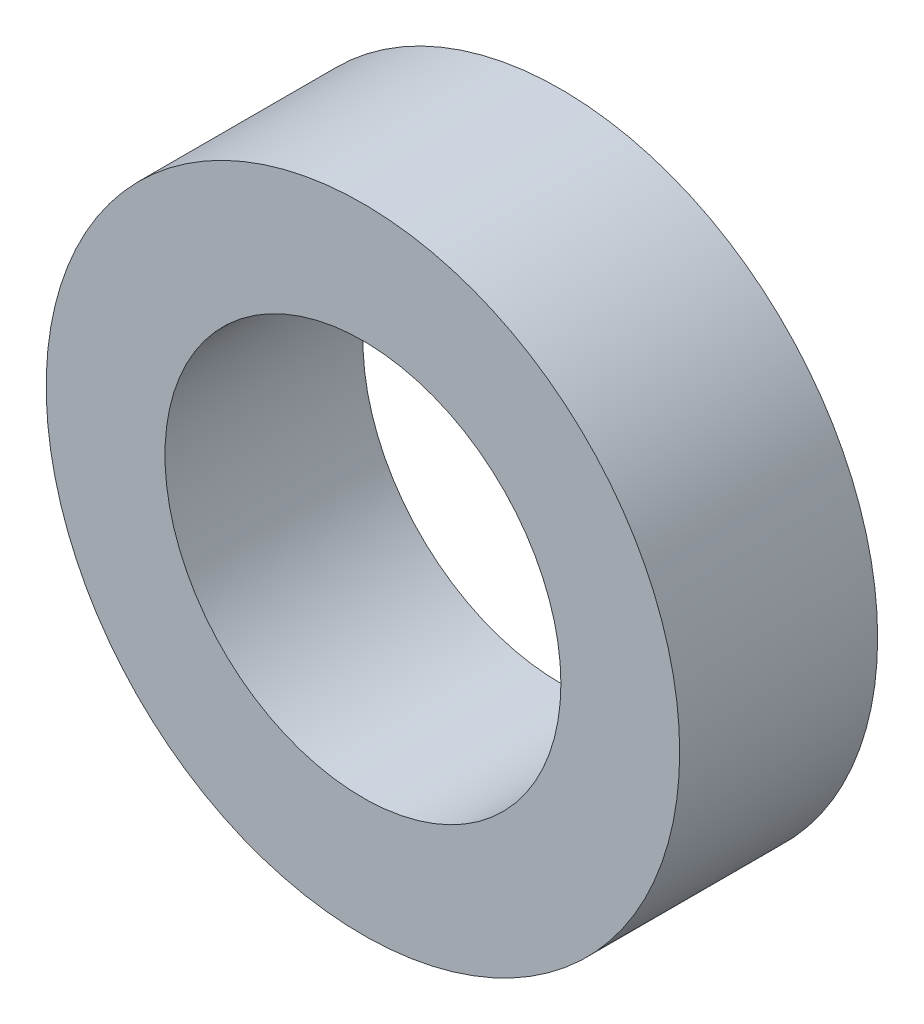
SolidWorks part; units mm, degrees
ref_plane "Front Plane" through (0, 0, 0) normal (0, 0, 1) x (1, 0, 0)
ref_plane "Top Plane" through (0, 0, 0) normal (0, 1, 0) x (1, 0, 0)
ref_plane "Right Plane" through (0, 0, 0) normal (1, 0, 0) x (0, 0, -1)
sketch "Sketch1" plane through (0, 0, 0) normal (0, 0, 1) x (1, 0, 0)
  circle A0 centre (0, 0) radius 4
  circle A1 centre (0, 0) radius 2.5
  dimension "D1" = 5
  dimension "D2" = 8
extrude "Boss-Extrude1" add sketch "Sketch1" along normal blind 2.5
equation "\"Ns\"= 24"
equation "\"Nr\"= 78"
equation "\"num_planet\"= 3"
equation "\"module\"= 0.6"
equation "\"pressure angle\"= 20.0"
equation "\"h_a\"= 0.6"
equation "\"h_b\"= 0.75"
equation "\"clr_tip_root\"= 0.15000000000000002"
equation "\"dp_s\"= 14.399999999999999"
equation "\"db_s\"= 13.53157373931708"
equation "\"fw_s_calc\"= 16.210783717444997"
equation "\"alpha_s\"= 0.8539582918412343"
equation "\"beta_s\"= 5.792083416317531"
equation "\"pressure_angle\"= 20.0"
equation "\"h_f\"= 0.75"
equation "\"dp_r\"= 46.8"
equation "\"db_r\"= 43.97761465278051"
equation "\"fw_r\"= 22.845791438896047"
equation "\"alpha_r\"= 0.8539582918412556"
equation "\"beta_r\"= 4.015608891374819"
equation "\"bearing_ID\"= 45"
equation "\"bearing_OD\"= 58"
equation "\"bearing_height\"= 7"
equation "\"clearance_planet\"= 1.5"
equation "\"case_dist\"= 24.210783717444997"
equation "\"Motor_case_OD_max\"= 88.5"
equation "\"case_mounting_PCD\"= 81.0"
equation "\"bearing mount thickness\"= IIF((\"bearing_OD\" + \"output_mounting_hole_dia\" * 4) > (\"Nr\" * \"module\" + 2 * \"h_b\"), \"output_mounting_hole_dia\" * 2, ((\"Nr\" * \"module\" + 2 * \"h_b\" - (\"bearing_OD\" + \"output_mounting_hole_dia\" * 4)) / 2) + \"output_mounting_hole_dia\" * 2 + \"standard_clearance_1_5mm\")"
equation "\"case_mounting_hole_dia\"= 3"
equation "\"output_mounting_PCD\"= 66"
equation "\"output_mounting_hole_dia\"= 4"
equation "\"clearance_case_mount_holes_shell_thickness\"= 1"
equation "\"motor_case_OD_base\"= 79.0"
equation "\"sec_carrier_thickness\"= 5"
equation "\"sun_coupler_hub_thickness\"= 4"
equation "\"clearance_sun_coupler_sec_carrier\"= 1.5"
equation "\"clearance_motor_and_case\"= 5"
equation "\"motor_OD\"= 64"
equation "\"Motor_case_thickness\"= 2.5"
equation "\"Motor_case_ID\"= 74"
equation "\"case_mounting_hole_shift\"= 1.0"
equation "\"output_mounting_nut_wrench_size\"= 7"
equation "\"output_mounting_nut_thickness\"= 3.2"
equation "\"case_mounting_hole_allen_socket_dia\"= 5.5"
equation "\"output_mounting_nut_depth\"= 3"
equation "\"case_mounting_bolt_depth\"= 4.5"
equation "\"ring_radial_thickness\"= 7.100000000000001"
equation "\"ring_OD\"= 61.0"
equation "\"ring_to_chamfer_clearance\"= 0.5"
equation "\"Motor_case_OD_base_to_chamfer\"= 5"
equation "\"pattern_offset_from_motor_case_OD_base\"= 3"
equation "\"pattern_bulge_dia\"= 3"
equation "\"pattern_num_bulge\"= 18"
equation "\"pattern_depth\"= 2"
equation "\"motor_height\"= 75"
equation "\"case_mounting_wrench_size\"= 5.5"
equation "\"case_mounting_nut_clearance\"= 2"
equation "\"base_plate_thickness\"= 4"
equation "\"case_mounting_nut_thickness\"= 2.4"
equation "\"case_mounting_surface_height\"= 4"
equation "\"motor_mount_hole_PCD\"= 44"
equation "\"motor_mount_hole_dia\"= 4"
equation "\"motor_mount_hole_num\"= 4"
equation "\"central_hole_offset_from_motor_mount_PCD\"= 5"
equation "\"wire_slot_dist_from_center\"= 22"
equation "\"wire_slot_length\"= 8"
equation "\"wire_slot_radius\"= 2"
equation "\"driver_upper_holes_dist_from_center\"= 29"
equation "\"driver_lower_holes_dist_from_center\"= 13"
equation "\"driver_side_holes_dist_from_center\"= 22.5"
equation "\"driver_mount_holes_dia\"= 3"
equation "\"driver_mount_inserts_OD\"= 4.8"
equation "\"driver_mount_thickness\"= 1.5"
equation "\"driver_mount_height\"= 6"
equation "\"air_flow_hole_offset\"= 3"
equation "\"planet_pin_bolt_dia\"= 2.5"
equation "\"planet_pin_socket_head_dia\"= 4.5"
equation "\"carrier_PCD\"= 34.199999999999996"
equation "\"planet_shaft_dia\"= 5"
equation "\"planet_shaft_step_offset\"= 0.8"
equation "\"carrier_trapezoidal_support_sun_offset\"= 5"
equation "\"carrier_trapezoidal_support_hole_PCD_offset_bearing_ID\"= 4"
equation "\"carrier_trapezoidal_support_hole_dia\"= 3"
equation "\"carrier_trapezoidal_support_hole_socket_head_dia\"= 5.5"
equation "\"carrier_bearing_step_width\"= 1.5"
equation "\"standard_clearance_1_5mm\"= 1.5"
equation "\"standard_fillet_1_5mm\"= 1.5"
equation "\"sun_shaft_bearing_OD\"= 14"
equation "\"sun_shaft_bearing_width\"= 5"
equation "\"standard_bearing_insertion_chamfer\"= 0.5"
equation "\"carrier_trapezoidal_support_hole_wrench_size\"= 5.5"
equation "\"planet_pin_bolt_wrench_size\"= 5"
equation "\"planet_bearing_OD\"= 8"
equation "\"planet_bearing_width\"= 2.5"
equation "\"planet_bore\"= 6"
equation "\"motor_output_hole_PCD\"= 32"
equation "\"motor_output_hole_dia\"= 4"
equation "\"motor_output_hole_num\"= 4"
equation "\"sun_shaft_bearing_ID\"= 7"
equation "\"sun_hub_dia\"= 42.0"
equation "\"sun_central_bolt_dia\"= 3"
equation "\"sun_central_bolt_socket_head_dia\"= 5.5"
equation "\"fw_s_used\"= 48.55657515634104"
equation "\"motor_output_hole_CSK_OD\"= 8"
equation "\"motor_output_hole_CSK_head_height\"= 2.0"
equation "\"D1@Sketch1\"=\"planet_shaft_dia\""
equation "\"D2@Sketch1\"=\"planet_bearing_OD\""
equation "\"D1@Boss-Extrude1\"=\"planet_bearing_width\""
equation "\"Np_b\"= 33"
equation "\"dp_p_b\"= 19.8"
equation "\"db_p_b\"= 18.605913891560988"
equation "\"fw_p_s\"= 24.345791438896047"
equation "\"alpha_p_b\"= 0.8539582918412414"
equation "\"beta_p_b\"= 3.7466288708629714"
equation "\"bearing_retainer_thickness\"= 2"
equation "\"Np_s\"= 21"
equation "\"fw_p_b\"= 16.210783717444997"
equation "\"dp_p_s\"= 12.6"
equation "\"db_p_s\"= 11.840127021902445"
equation "\"alpha_p_s\"= 0.8539582918412556"
equation "\"beta_p_s\"= 6.86351198774606"
